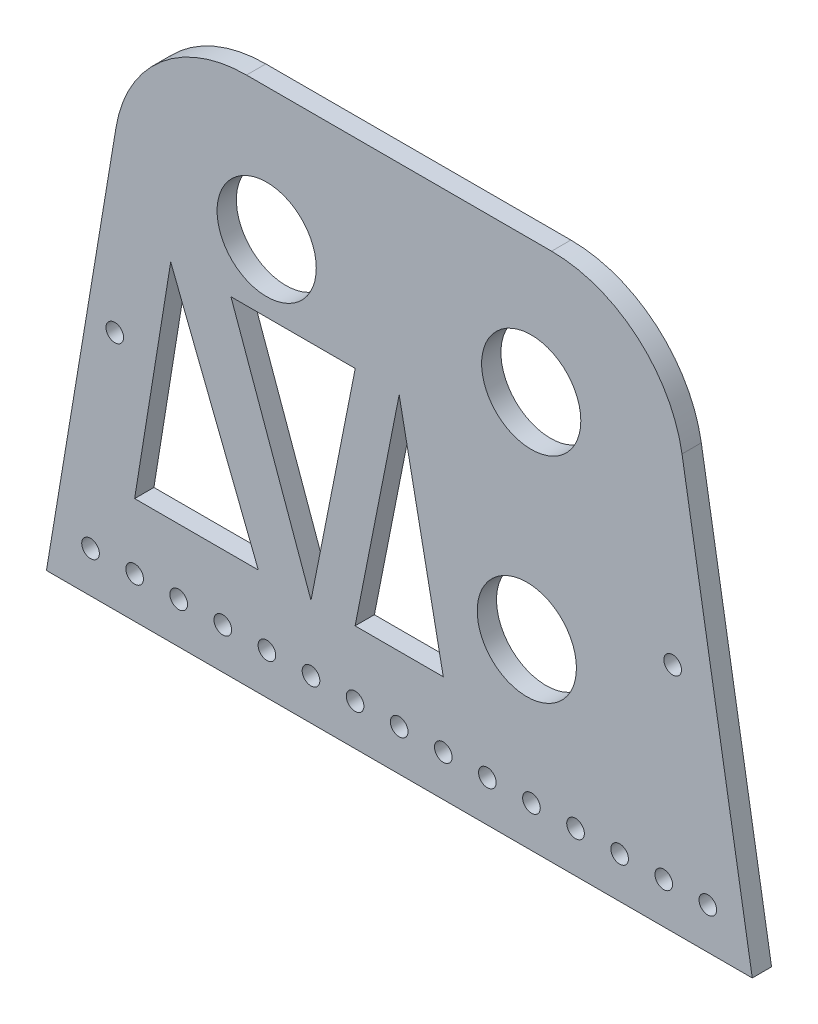
SolidWorks part; units mm, degrees
ref_plane "Front Plane" through (0, 0, 0) normal (0, 0, 1) x (1, 0, 0)
ref_plane "Top Plane" through (0, 0, 0) normal (0, 1, 0) x (1, 0, 0)
ref_plane "Right Plane" through (0, 0, 0) normal (1, 0, 0) x (0, 0, -1)
sketch "Sketch2" plane through (0, 0, 0) normal (0, 0, 1) x (1, 0, 0)
  line L0 (-33.222, -123.0337) -> (-58.5557, -123.0337)
  line L1 (-33.222, 29.3663) -> (119.178, 29.3663)
  line L3 (-33.222, -123.0337) -> (119.178, -123.0337)
  line L5 (-58.5557, -123.0337) -> (-33.222, 29.3663)
  line L6 (119.178, -123.0337) -> (144.7459, -123.0337)
  line L7 (144.7459, -123.0337) -> (119.178, 29.3663)
  line L8 (-22.7678, -28.1678) -> (-33.1557, -92.3946)
  line L9 (-33.1557, -92.3946) -> (2.468, -92.3946)
  line L10 (2.468, -92.3946) -> (-22.7678, -28.1678)
  line L14 (43.0443, -28.3997) -> (55.7443, -92.3946)
  line L15 (55.7443, -92.3946) -> (30.3443, -92.3946)
  line L16 (30.3443, -92.3946) -> (43.0443, -28.3997)
  line L20 (17.6443, -92.3946) -> (30.3903, -28.1678)
  line L21 (30.3903, -28.1678) -> (-5.4154, -28.1678)
  line L22 (-5.4154, -28.1678) -> (17.6443, -92.3946)
  circle A0 centre (4.878, -8.7337) radius 14.2875
  circle A1 centre (81.078, -8.7337) radius 14.2875
  circle A2 centre (-45.8557, -111.1877) radius 2.54
  circle A3 centre (-33.1557, -111.1877) radius 2.54
  circle A4 centre (-20.4557, -111.1877) radius 2.54
  circle A5 centre (-7.7557, -111.1877) radius 2.54
  circle A6 centre (4.9443, -111.1877) radius 2.54
  circle A7 centre (17.6443, -111.1877) radius 2.54
  circle A8 centre (30.3443, -111.1877) radius 2.54
  circle A9 centre (43.0443, -111.1877) radius 2.54
  circle A10 centre (55.7443, -111.1877) radius 2.54
  circle A11 centre (68.4443, -111.1877) radius 2.54
  circle A12 centre (81.1443, -111.1877) radius 2.54
  circle A13 centre (93.8443, -111.1877) radius 2.54
  circle A14 centre (106.5443, -111.1877) radius 2.54
  circle A15 centre (119.2443, -111.1877) radius 2.54
  circle A16 centre (131.9443, -111.1877) radius 2.54
  circle A17 centre (79.8095, -71.0514) radius 14.2875
  circle A18 centre (121.8106, -56.3701) radius 2.54 construction
  circle A19 centre (-38.8741, -53.8301) radius 2.54 construction
  circle A20 centre (121.8106, -56.3701) radius 2.54
  circle A21 centre (-38.8741, -53.8301) radius 2.54
  dimension "D3" = 28.575
  dimension "D4" = 28.575
  dimension "D9" = 15
  dimension "D10" = 12.7
  dimension "D11" = 28.575
  dimension "D1" = 152.4
  dimension "D2" = 152.4
  dimension "D5" = 76.2
  dimension "D6" = 38.1
  dimension "D7" = 38.1
  dimension "D8" = 38.1
extrude "Boss-Extrude1" add sketch "Sketch2" along normal blind 5.5562
fillet "Fillet1" radius 38.1 2 edges at (-33.222, 29.3663, 2.7781) (119.178, 29.3663, 2.7781)
